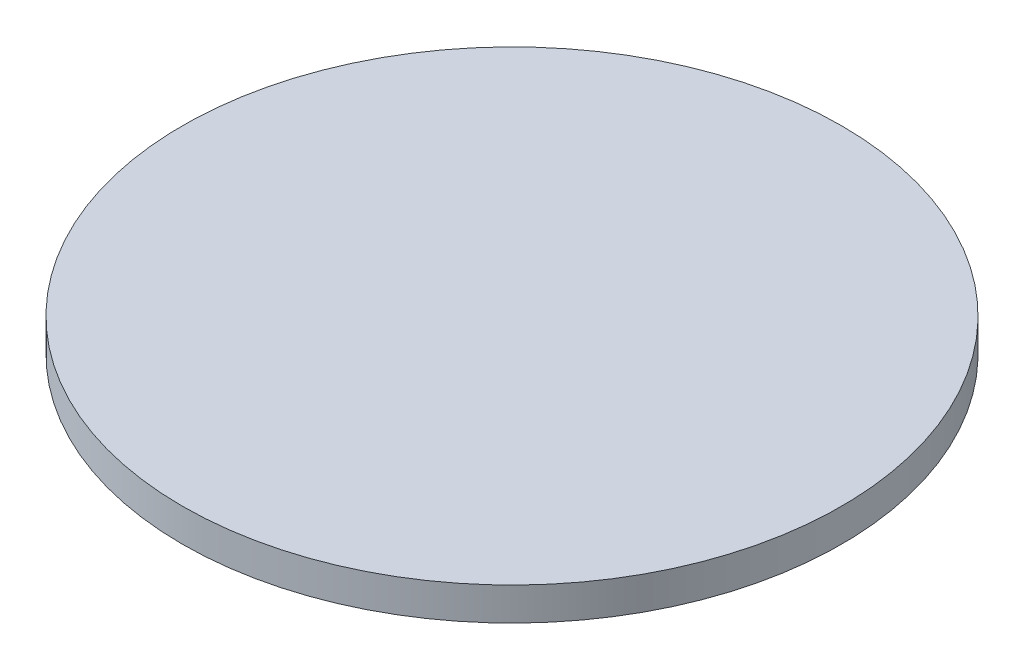
SolidWorks part; units mm, degrees
material "CA"
ref_plane "Plan de face" through (0, 0, 0) normal (0, 0, 1) x (1, 0, 0)
ref_plane "Plan de dessus" through (0, 0, 0) normal (0, 1, 0) x (1, 0, 0)
ref_plane "Plan de droite" through (0, 0, 0) normal (1, 0, 0) x (0, 0, -1)
sketch "Esquisse1" plane through (0, 0, 0) normal (0, 1, 0) x (1, 0, 0)
  circle A0 centre (-5.7797, 0) radius 25
  dimension "D1" = 50
extrude "Boss.-Extru.1" add sketch "Esquisse1" along normal blind 6
chamfer "Chanfrein1" distance 6 distance2 3.5 1 edges at (-5.7797, 0, 25)
